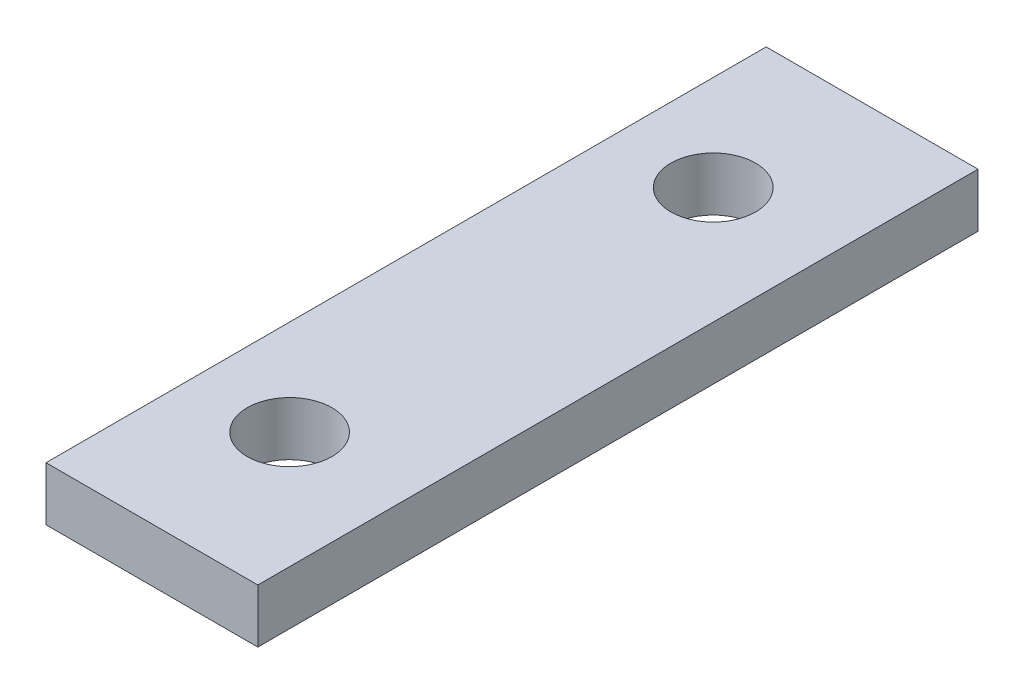
SolidWorks part; units mm, degrees
material "Aleación 1060"
ref_plane "Alzado" through (0, 0, 0) normal (0, 0, 1) x (1, 0, 0)
ref_plane "Planta" through (0, 0, 0) normal (0, 1, 0) x (1, 0, 0)
ref_plane "Vista lateral" through (0, 0, 0) normal (1, 0, 0) x (0, 0, -1)
sketch "Croquis1" plane through (0, 0, 0) normal (0, 1, 0) x (1, 0, 0)
  line L0 (-2.5, 124.5738) -> (-2.5, -130.7049) construction
  line L1 (-25, -85) -> (25, -85)
  line L2 (-25, -85) -> (-25, 85)
  line L3 (-25, 85) -> (25, 85)
  line L4 (25, -85) -> (25, 85)
  line L5 (-25, -85) -> (25, 85) construction
  line L6 (-25, 85) -> (25, -85) construction
  circle A0 centre (-2.5, 50) radius 10
  circle A1 centre (-2.5, -50) radius 10
  point P0 (0, 0)
  dimension "D4" = 20
  dimension "D6" = 20
  dimension "D1" = 170
  dimension "D2" = 50
  dimension "D3" = 27.5
  dimension "D5" = 50
  dimension "D7" = 50
extrude "Saliente-Extruir1" add sketch "Croquis1" along normal blind 12.7
equation "\"D6@Croquis1\"=\"D4@Croquis1\""
equation "\"D7@Croquis1\"=\"D5@Croquis1\""
